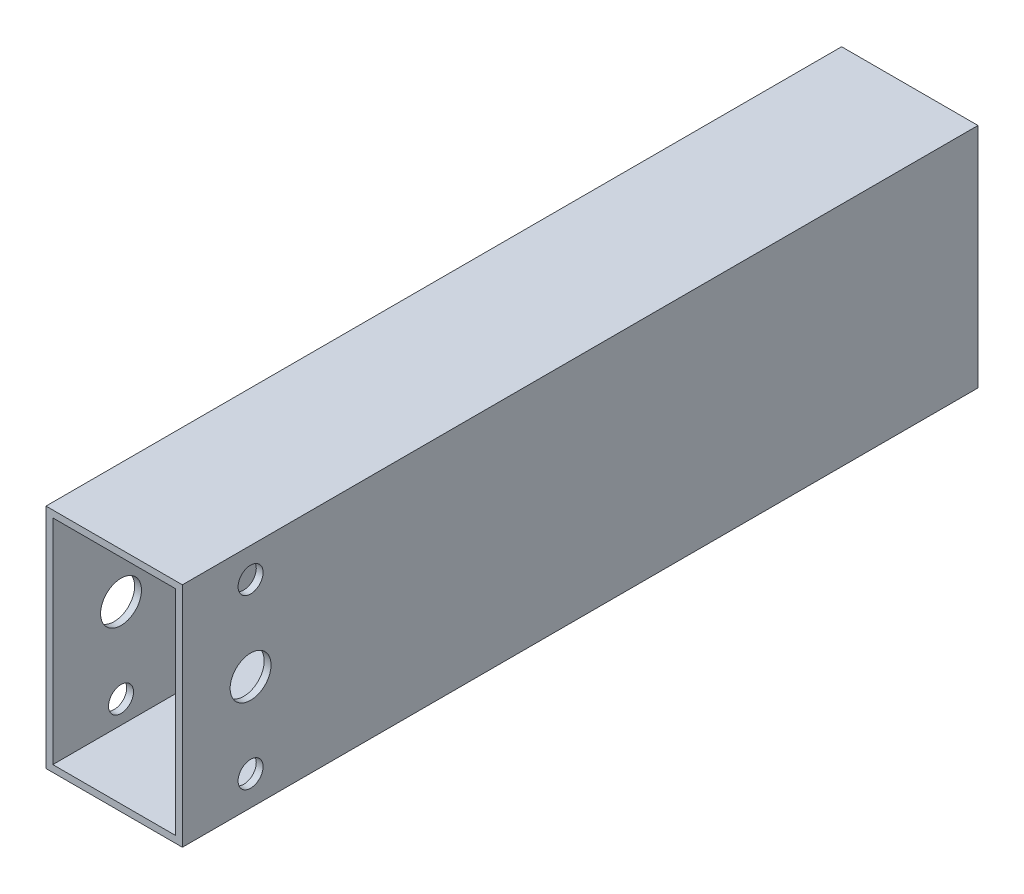
SolidWorks part; units mm, degrees
ref_plane "Plano frontal" through (0, 0, 0) normal (0, 0, 1) x (1, 0, 0)
ref_plane "Plano superior" through (0, 0, 0) normal (0, 1, 0) x (1, 0, 0)
ref_plane "Plano direito" through (0, 0, 0) normal (1, 0, 0) x (0, 0, -1)
sketch "Esboço1" plane through (0, 0, 0) normal (0, 0, 1) x (1, 0, 0)
  line L1 (0, 0) -> (30, 0)
  line L2 (0, 0) -> (0, 50)
  line L3 (0, 50) -> (30, 50)
  line L4 (30, 0) -> (30, 50)
  line L5 (1.5, 1.5) -> (28.5, 1.5)
  line L6 (1.5, 1.5) -> (1.5, 48.5)
  line L7 (1.5, 48.5) -> (28.5, 48.5)
  line L8 (28.5, 1.5) -> (28.5, 48.5)
  dimension "D1" = 50
  dimension "D2" = 30
  dimension "D3" = 1.5
  dimension "D4" = 1.5
  dimension "D5" = 1.5
  dimension "D6" = 1.5
extrude "Ressalto-extrusão1" add sketch "Esboço1" along normal blind 175
hole_wizard "Furo com folga de M53" positions "Esboço21" profile "Esboço20" hole size "M5" standard "ISO"
sketch "Esboço21" plane through (30, 0, 0) normal (1, 0, 0) x (0, 0, -1)
  line L0 (-175, 25) -> (-1430.3278, 25) construction
  line L1 (-175, 0) -> (-175, 50) construction
  point P0 (-160, 43.5)
  point P2 (-160, 6.5)
  dimension "D1" = 15
  dimension "D2" = 18.5
sketch "Esboço20" plane through (30, 43.5, 160) normal (0, 1, 0) x (0, 0, -1)
  line L0 (0, 0) -> (0, 31.6524)
  line L1 (0, 31.6524) -> (2.75, 30)
  line L2 (2.75, 30) -> (2.75, 0)
  line L5 (2.75, 0) -> (0, 0)
  line L10 (0, 31.6524) -> (-2.75, 30) construction
  line L11 (0, -6.35) -> (0, 107.95) construction
  dimension "Hole Dia." = 5.5
  dimension "Hole Depth" = 30
  dimension "Drill Angle" = 118
hole_wizard "Furo com folga de M85" positions "Esboço24" profile "Esboço22" hole size "M8" standard "ISO"
sketch "Esboço24" plane through (30, 0, 0) normal (1, 0, 0) x (0, 0, -1)
  line L0 (-175, 25) -> (-1424.6143, 25) construction
  line L1 (-175, 0) -> (-175, 50) construction
  point P0 (-160, 25)
  dimension "D1" = 15
sketch "Esboço22" plane through (30, 25, 160) normal (0, 1, 0) x (0, 0, -1)
  line L0 (0, 0) -> (0, 32.7039)
  line L1 (0, 32.7039) -> (4.5, 30)
  line L2 (4.5, 30) -> (4.5, 0)
  line L5 (4.5, 0) -> (0, 0)
  line L10 (0, 32.7039) -> (-4.5, 30) construction
  line L11 (0, -6.35) -> (0, 107.95) construction
  dimension "Hole Dia." = 9
  dimension "Hole Depth" = 30
  dimension "Drill Angle" = 118
